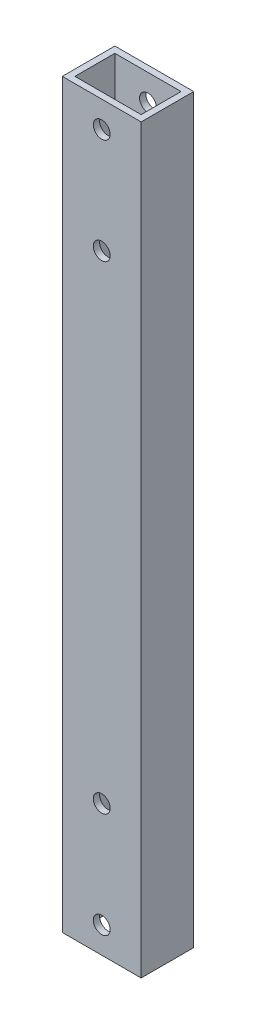
SolidWorks part; units mm, degrees
ref_plane "正面" through (0, 0, 0) normal (0, 0, 1) x (1, 0, 0)
ref_plane "平面" through (0, 0, 0) normal (0, 1, 0) x (1, 0, 0)
ref_plane "右側面" through (0, 0, 0) normal (1, 0, 0) x (0, 0, -1)
sketch "ｽｹｯﾁ1" plane through (0, 0, 0) normal (0, 1, 0) x (1, 0, 0)
  line L0 (-6.3, 3.8) -> (6.3, 3.8)
  line L1 (-7.5, 5) -> (7.5, 5)
  line L2 (-7.5, 5) -> (-7.5, -5)
  line L3 (-7.5, -5) -> (7.5, -5)
  line L4 (7.5, 5) -> (7.5, -5)
  line L5 (-7.5, 5) -> (7.5, -5) construction
  line L6 (-7.5, -5) -> (7.5, 5) construction
  line L7 (6.3, 3.8) -> (6.3, -3.8)
  line L8 (-6.3, -3.8) -> (6.3, -3.8)
  line L9 (-6.3, 3.8) -> (-6.3, -3.8)
  point P0 (0, 0)
  dimension "D1" = 15
  dimension "D2" = 10
  dimension "D3" = 1.2
extrude "ﾎﾞｽ - 押し出し1" add sketch "ｽｹｯﾁ1" along normal mid plane 141
sketch "ｽｹｯﾁ2" plane through (0, 0, -5) normal (0, 0, -1) x (-1, 0, 0)
  line L0 (0, 0) -> (-7.5, 0) construction
  line L1 (-7.5, 70.5) -> (-7.5, -70.5) construction
  line L2 (0, 0) -> (0, -70.5) construction
  line L3 (-7.5, -70.5) -> (7.5, -70.5) construction
  circle A0 centre (0, -65.5) radius 1.6
  circle A1 centre (0, -45.5) radius 1.6
  circle A2 centre (0, 45.5) radius 1.6
  circle A3 centre (0, 65.5) radius 1.6
  dimension "D1" = 3.2
  dimension "D2" = 3.2
  dimension "D3" = 5
  dimension "D4" = 20
extrude "ｶｯﾄ - 押し出し1" cut sketch "ｽｹｯﾁ2" against normal blind 100
